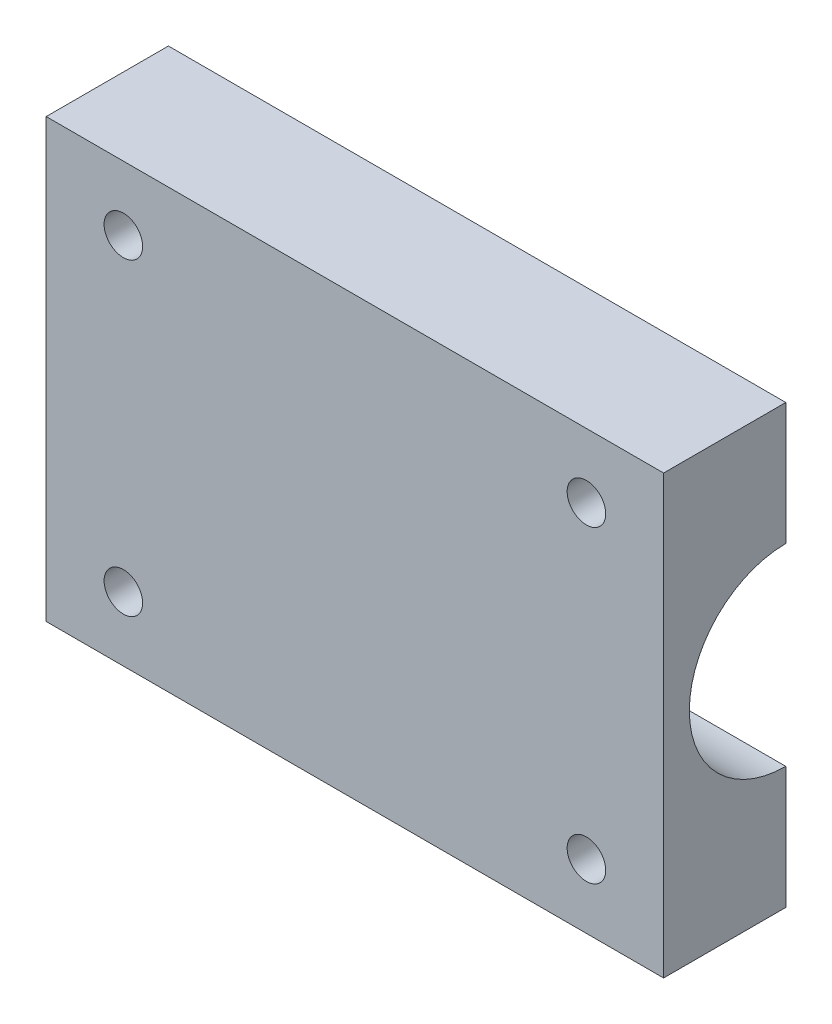
SolidWorks part; units mm, degrees
ref_plane "前视基准面" through (0, 0, 0) normal (0, 0, 1) x (1, 0, 0)
ref_plane "上视基准面" through (0, 0, 0) normal (0, 1, 0) x (1, 0, 0)
ref_plane "右视基准面" through (0, 0, 0) normal (1, 0, 0) x (0, 0, -1)
sketch "草图1" plane through (0, 0, 0) normal (0, 0, 1) x (1, 0, 0)
  line L0 (-24.0429, -0.3643) -> (23.9571, -0.3643) construction
  line L1 (-24.0429, 16.6357) -> (23.9571, 16.6357)
  line L2 (-24.0429, 16.6357) -> (-24.0429, -17.3643)
  line L3 (-24.0429, -17.3643) -> (23.9571, -17.3643)
  line L4 (23.9571, 16.6357) -> (23.9571, -17.3643)
  line L5 (-18.0429, 11.6357) -> (-18.0429, -12.3643)
  line L6 (17.9571, 11.6357) -> (17.9571, -12.3643)
  circle A0 centre (-18.0429, 11.6357) radius 1.5
  circle A1 centre (17.9571, 11.6357) radius 1.5
  circle A2 centre (-18.0429, -12.3643) radius 1.5
  circle A3 centre (17.9571, -12.3643) radius 1.5
  point P6 (-18.0429, -0.3643)
  point P7 (17.9571, -0.3643)
  point P11 (-18.0429, -0.3643)
  point P14 (17.9571, -0.3643)
  dimension "D1" = 34
  dimension "D2" = 48
  dimension "D3" = 6
  dimension "D4" = 6
  dimension "D5" = 24
  dimension "D6" = 24
extrude "凸台-拉伸1" add sketch "草图1" along normal blind 9.5
sketch "草图2" plane through (23.9571, 0, 0) normal (1, 0, 0) x (0, 0, -1)
  line L0 (0, 16.6357) -> (0, -17.3643) construction
  circle A0 centre (0, -0.3643) radius 7.5
extrude "切除-拉伸1" cut sketch "草图2" against normal blind 54.5
